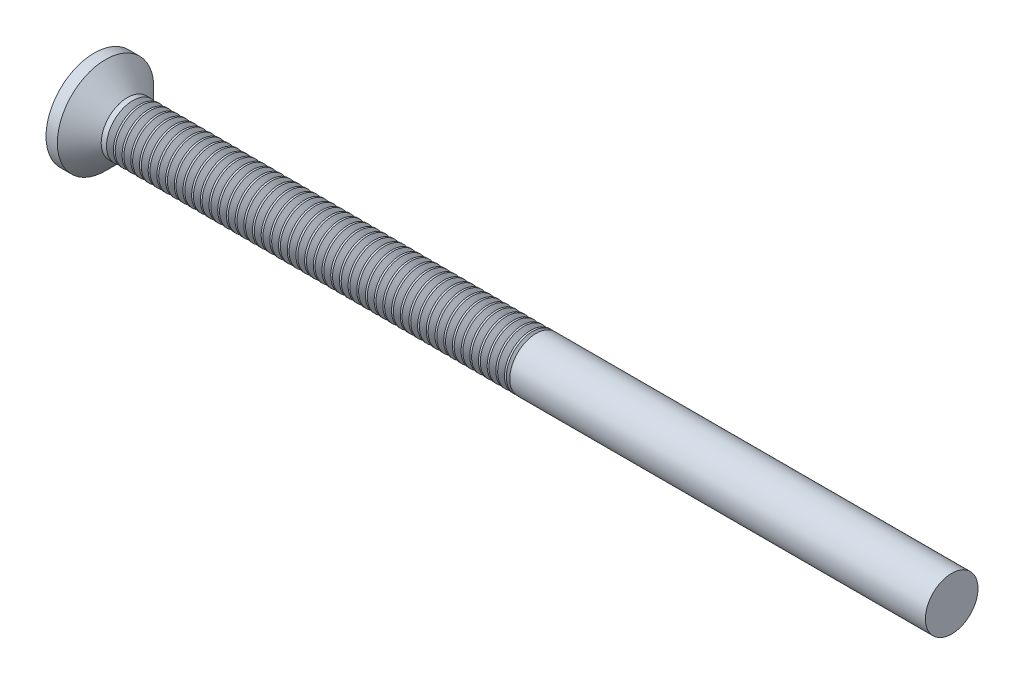
SolidWorks part; units mm, degrees
revolve "Base-Revolve" add sketch "BodySke" angle 360 about L4
sketch "BodySke" plane through (0, 0, 0) normal (0, 0, 1) x (1, 0, 0)
  line L0 (0, 0) -> (25.7277, 0)
  line L1 (25.7277, 0) -> (25.7277, 1.5)
  line L2 (25.7277, 1.5) -> (2.4277, 1.5)
  line L3 (2.4277, 1.5) -> (-7.1953, 11.123) construction
  line L4 (-15.875, 0) -> (82.55, 0) construction
  line L5 (2.4277, -1.5) -> (-7.1953, -11.123) construction
  line L6 (2.9277, 4.675) -> (2.9277, -11.2) construction
  line L7 (0.7277, 8.7375) -> (0.7277, -7.1375) construction
  line L8 (2.4277, 1.5) -> (1.1777, 2.75)
  line L9 (1.1777, 2.75) -> (0.53, 2.75)
  arc A0 (0, 0) -> (0.53, 2.75) centre (7.4, 0) cw
  arc A1 (0.7277, 3.2) -> (0, 0) centre (7.4, 0) ccw construction
  dimension "Crown_rad" = 7.4
  dimension "Diameter" = 3
  dimension "Advance" = 0.5
  dimension "Thread_nom" = 25
  dimension "Head_ang" = 90
  dimension "D3" = 6.4
  dimension "Side_ht" = 1.7
  dimension "D4" = 0.7277
  dimension "Length" = 25
  dimension "Head_dia" = 5.5
cosmetic thread "ThreadCosmetic" [suppressed] parameters "Thread_length"=22.8, "Thread_minor"=2.439
ref_plane "Plane1" through (0, 0, 0) normal (0, 0, 1) x (1, 0, 0)
ref_plane "Plane2" through (0, 0, 0) normal (0, 1, 0) x (1, 0, 0)
ref_plane "Plane3" through (0, 0, 0) normal (1, 0, 0) x (0, 0, -1)
sketch "Sketch2" plane through (0, 0, 0) normal (1, 0, 0) x (0, 0, -1)
  line L0 (2.75, -0.5) -> (-2.75, -0.5)
  line L1 (2.75, -0.5) -> (2.75, 0.5)
  line L2 (-2.75, 0.5) -> (2.75, 0.5)
  line L3 (-2.75, 0.5) -> (-2.75, -0.5)
  dimension "D1" = 5.5
  dimension "Slot_width" = 1
  dimension "D3" = 2.75
  dimension "D4" = 0.5
extrude "Slot" [suppressed] cut sketch "Sketch2" along normal blind 1.5
sketch "Sketch3" plane through (0, 0, 0) normal (1, 0, 0) x (0, 0, -1)
  line L0 (0.415, -1.72) -> (-0.415, -1.72)
  line L1 (0.415, -1.72) -> (0.415, 1.72)
  line L2 (-0.415, 1.72) -> (0.415, 1.72)
  line L3 (-0.415, 1.72) -> (-0.415, -1.72)
  dimension "Cross_width" = 0.83
  dimension "D1" = 0.415
  dimension "Cross_dia" = 3.44
  dimension "D2" = 1.72
ref_plane "Plane4" through (2.33, 0, 0) normal (1, 0, 0) x (0, 0, -1)
sketch "Sketch4" plane through (2.33, 0, 0) normal (1, 0, 0) x (0, 0, -1)
  line L0 (0.2075, -0.2075) -> (-0.2075, -0.2075)
  line L1 (0.2075, -0.2075) -> (0.2075, 0.2075)
  line L2 (-0.2075, 0.2075) -> (0.2075, 0.2075)
  line L3 (-0.2075, 0.2075) -> (-0.2075, -0.2075)
  dimension "D1" = 0.415
  dimension "D2" = 0.415
  dimension "D3" = 0.2075
  dimension "D4" = 0.2075
loft "Cross" cut profiles "Sketch3", "Sketch4"
pattern_circular "CirPattern1" count 2 every 90 about axis through (0, 0, 0) along (1, 0, 0) of "Cross"
sketch "ThdSchSke" plane through (0, 0, 0) normal (0, 0, 1) x (1, 0, 0)
  line L0 (2.9277, -1.2195) -> (2.7313, -1.5)
  line L1 (2.9277, -1.2195) -> (3.1241, -1.5)
  line L2 (3.1241, -1.5) -> (3.1241, -1.875)
  line L3 (-3.175, 0) -> (5.1513, 0) construction
  line L5 (3.1241, -1.875) -> (2.7313, -1.875)
  line L6 (2.7313, -1.875) -> (2.7313, -1.5)
  line L8 (25.7277, -1.5) -> (25.7277, 1.5) construction
  dimension "Diameter" = 3
  dimension "Thread_minor" = 2.439
  dimension "Start" = 22.8
revolve "ThreadSchematic" cut sketch "ThdSchSke" angle 360 about L3
pattern_linear "ThdSchPat" count 47 spacing 0.4957 along (1, 0, 0) of "ThreadSchematic"
sketch "Croquis2" plane through (25.7277, 0, 0) normal (1, 0, 0) x (0, 0, -1)
  circle A0 centre (0, 0) radius 1.5
extrude "Saliente-Extruir1" add sketch "Croquis2" along normal blind 23.7
equation "\"D1@Sketch2\" = \"Head_dia@BodySke\""
equation "\"D3@Sketch2\" = \"D1@Sketch2\" / 2"
equation "\"D4@Sketch2\" = \"Slot_width@Sketch2\" / 2"
equation "\"D1@Sketch3\" = \"Cross_width@Sketch3\" / 2"
equation "\"D2@Sketch3\" = \"Cross_dia@Sketch3\" / 2"
equation "\"D1@Sketch4\" = \"Cross_width@Sketch3\"*.5"
equation "\"D2@Sketch4\" = \"D1@Sketch4\""
equation "\"D3@Sketch4\" = \"D1@Sketch4\" / 2"
equation "\"D4@Sketch4\" = \"D2@Sketch4\" / 2"
equation "\"Thread_length@ThreadCosmetic\" = ((sgn( (\"Length@BodySke\" - \"Advance@BodySke\" - \"Side_ht@BodySke\" ) - \"Thread_nom@BodySke\" )-1)*( (\"Length@BodySke\" - \"Advance@BodySke\" - \"Side_ht@BodySke\" ) - \"Thread_nom@BodySke\" ))/-2+ \"Thread_nom@BodySke\""
equation "\"Thread_minor@ThdSchSke\" = \"Thread_minor@ThreadCosmetic\""
equation "\"Diameter@ThdSchSke\" = \"Diameter@BodySke\""
equation "\"Overcut@ThdSchSke\" = \"Diameter@BodySke\" * 1.25"
equation "\"Start@ThdSchSke\" =  \"Thread_length@ThreadCosmetic\""
equation "\"Num_threads@ThdSchPat\" = int( \"Thread_length@ThreadCosmetic\" / \"Advance@BodySke\" + 0.999 )  + 1"
equation "\"Advance@ThdSchPat\" = \"Thread_length@ThreadCosmetic\" /  (\"Num_threads@ThdSchPat\" - 1) 'relax it"
